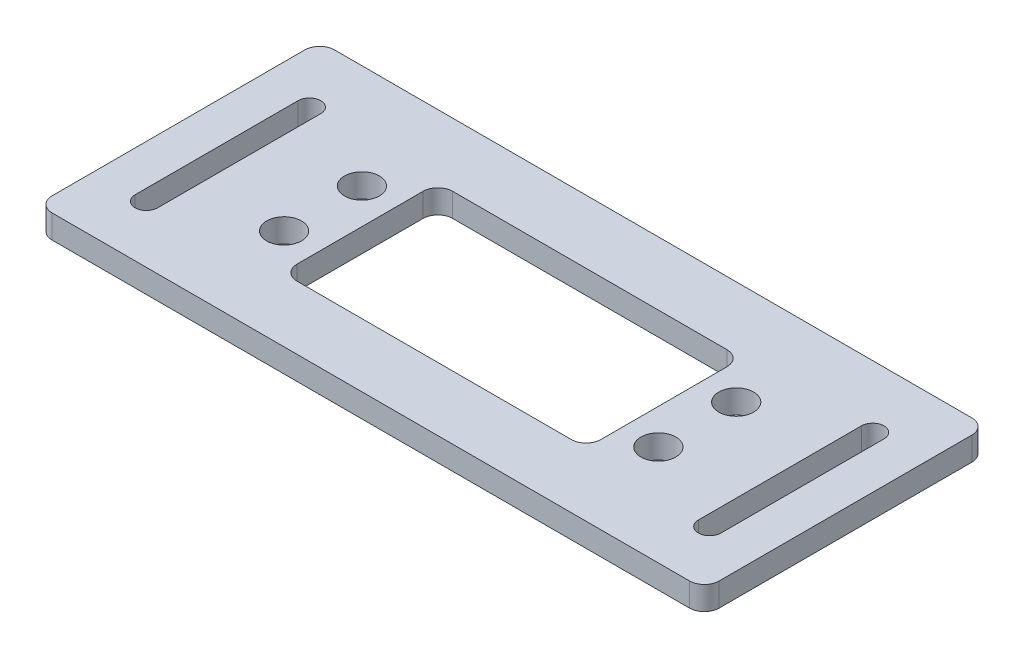
SolidWorks part; units mm, degrees
ref_plane "Front Plane" through (0, 0, 0) normal (0, 0, 1) x (1, 0, 0)
ref_plane "Top Plane" through (0, 0, 0) normal (0, 1, 0) x (1, 0, 0)
ref_plane "Right Plane" through (0, 0, 0) normal (1, 0, 0) x (0, 0, -1)
sketch "Sketch1" plane through (0, 0, 0) normal (0, 1, 0) x (1, 0, 0)
  line L1 (45, -19.05) -> (-45, -19.05)
  line L2 (45, -19.05) -> (45, 19.05)
  line L3 (45, 19.05) -> (-45, 19.05)
  line L4 (-45, -19.05) -> (-45, 19.05)
  line L5 (45, -19.05) -> (-45, 19.05) construction
  line L6 (45, 19.05) -> (-45, -19.05) construction
  point P0 (0, 0)
  dimension "D1" = 90
  dimension "D2" = 38.1
extrude "Boss-Extrude1" add sketch "Sketch1" along normal blind 3.175
sketch "Sketch2" plane through (0, 3.175, 0) normal (0, 1, 0) x (1, 0, 0)
  line L0 (0, 19.05) -> (0, -19.05) construction
  line L1 (45, 19.05) -> (-45, 19.05) construction
  line L2 (-45, -19.05) -> (45, -19.05) construction
  line L3 (-25.25, 15.1128) -> (25.25, 15.1128) construction
  line L4 (20.5, -10.5) -> (-20.5, -10.5)
  line L5 (20.5, -10.5) -> (20.5, 10.5)
  line L6 (20.5, 10.5) -> (-20.5, 10.5)
  line L7 (-20.5, -10.5) -> (-20.5, 10.5)
  line L8 (20.5, -10.5) -> (-20.5, 10.5) construction
  line L9 (20.5, 10.5) -> (-20.5, -10.5) construction
  line L10 (-45, 0) -> (45, 0) construction
  line L11 (-45, 19.05) -> (-45, -19.05) construction
  line L12 (45, -19.05) -> (45, 19.05) construction
  line L13 (-25.25, -5) -> (-25.25, 5) construction
  circle A0 centre (-25.25, 5) radius 2.35
  circle A1 centre (-25.25, -5.5033) radius 2.35
  circle A2 centre (25.25, 5) radius 2.35
  circle A3 centre (25.25, -5.5033) radius 2.35
  point P6 (0, 0)
  point P14 (0, 15.1128)
  point P23 (-25.25, 0)
  dimension "D4" = 4.7
  dimension "D1" = 41
  dimension "D2" = 50.5
  dimension "D3" = 10
  dimension "D5" = 21
extrude "Cut-Extrude1" cut sketch "Sketch2" against normal through all
fillet "Fillet1" radius 2 8 edges at (20.5, 1.5875, -10.5) (20.5, 1.5875, 10.5) (-20.5, 1.5875, 10.5) (-20.5, 1.5875, -10.5) (-45, 1.5875, -19.05) (45, 1.5875, -19.05) (45, 1.5875, 19.05) (-45, 1.5875, 19.05)
sketch "Sketch3" plane through (0, 3.175, 0) normal (0, 1, 0) x (1, 0, 0)
  line L0 (-38, 10.67) -> (-38, -11.33) construction
  line L1 (-36.475, 10.67) -> (-36.475, -11.33)
  line L2 (-39.525, 10.67) -> (-39.525, -11.33)
  line L3 (-45, 17.05) -> (-45, -17.05) construction
  line L4 (0, -19.4442) -> (0, 22.1668) construction
  line L5 (38, 10.67) -> (38, -11.33) construction
  line L6 (36.475, 10.67) -> (36.475, -11.33)
  line L7 (39.525, 10.67) -> (39.525, -11.33)
  line L8 (-38, -0.33) -> (38, -0.33) construction
  arc A0 (-36.475, 10.67) -> (-39.525, 10.67) centre (-38, 10.67) ccw
  arc A1 (-39.525, -11.33) -> (-36.475, -11.33) centre (-38, -11.33) ccw
  arc A2 (36.475, 10.67) -> (39.525, 10.67) centre (38, 10.67) cw
  arc A3 (39.525, -11.33) -> (36.475, -11.33) centre (38, -11.33) cw
  point P2 (-38, -0.33)
  point P9 (38, -0.33)
  dimension "D2" = 1.525
  dimension "D1" = 22
  dimension "D3" = 7
extrude "Cut-Extrude2" cut sketch "Sketch3" against normal through all
